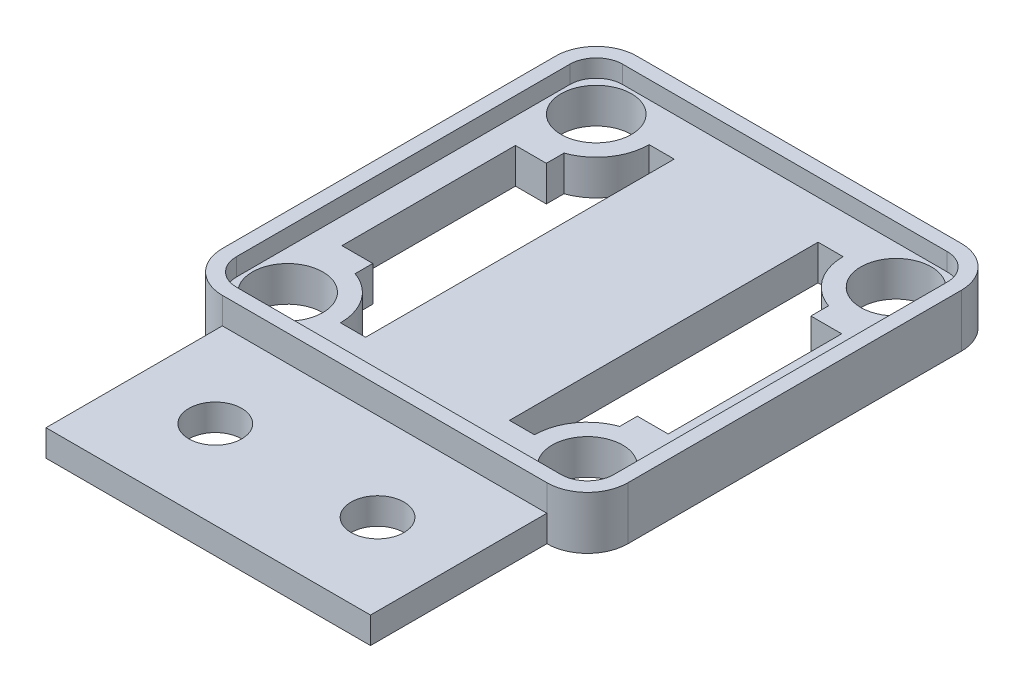
SolidWorks part; units mm, degrees
ref_plane "Front Plane" through (0, 0, 0) normal (0, 0, 1) x (1, 0, 0)
ref_plane "Top Plane" through (0, 0, 0) normal (0, 1, 0) x (1, 0, 0)
ref_plane "Right Plane" through (0, 0, 0) normal (1, 0, 0) x (0, 0, -1)
sketch "Sketch1" plane through (0, 0, 0) normal (0, 1, 0) x (1, 0, 0)
  line L1 (-12.6491, 14.6331) -> (5.7509, 14.6331)
  line L2 (-14.9491, 12.3331) -> (-14.9491, -6.5669)
  line L3 (-12.6491, -8.8669) -> (5.7509, -8.8669)
  line L4 (8.0509, 12.3331) -> (8.0509, -6.5669)
  line L5 (-14.9491, 14.6331) -> (8.0509, -8.8669) construction
  line L6 (-14.9491, -8.8669) -> (8.0509, 14.6331) construction
  arc A0 (8.0509, 12.3331) -> (5.7509, 14.6331) centre (5.7509, 12.3331) ccw
  arc A1 (-12.6491, -8.8669) -> (-14.9491, -6.5669) centre (-12.6491, -6.5669) cw
  arc A2 (5.7509, -8.8669) -> (8.0509, -6.5669) centre (5.7509, -6.5669) ccw
  arc A3 (-14.9491, 12.3331) -> (-12.6491, 14.6331) centre (-12.6491, 12.3331) cw
  point P0 (-3.4491, 2.8831)
  dimension "D3" = 2.3
  dimension "D4" = 2.3
  dimension "D1" = 23.5
  dimension "D2" = 23
extrude "Boss-Extrude1" add sketch "Sketch1" along normal blind 3
sketch "Sketch2" plane through (0, 3, 0) normal (0, 1, 0) x (1, 0, 0)
  line L8 (5.7509, 13.6331) -> (-12.6491, 13.6331)
  line L9 (-13.9491, 12.3331) -> (-13.9491, -6.5669)
  line L10 (-12.6491, -7.8669) -> (5.7509, -7.8669)
  line L11 (7.0509, -6.5669) -> (7.0509, 12.3331)
  line L12 (5.7509, 13.6331) -> (-12.6491, 13.6331)
  line L13 (-13.9491, 12.3331) -> (-13.9491, -6.5669)
  line L14 (-12.6491, -7.8669) -> (5.7509, -7.8669)
  line L15 (7.0509, -6.5669) -> (7.0509, 12.3331)
  arc A8 (7.0509, 12.3331) -> (5.7509, 13.6331) centre (5.7509, 12.3331) ccw
  arc A9 (-12.6491, 13.6331) -> (-13.9491, 12.3331) centre (-12.6491, 12.3331) ccw
  arc A10 (-13.9491, -6.5669) -> (-12.6491, -7.8669) centre (-12.6491, -6.5669) ccw
  arc A11 (5.7509, -7.8669) -> (7.0509, -6.5669) centre (5.7509, -6.5669) ccw
  arc A12 (7.0509, 12.3331) -> (5.7509, 13.6331) centre (5.7509, 12.3331) ccw
  arc A13 (-12.6491, 13.6331) -> (-13.9491, 12.3331) centre (-12.6491, 12.3331) ccw
  arc A14 (-13.9491, -6.5669) -> (-12.6491, -7.8669) centre (-12.6491, -6.5669) ccw
  arc A15 (5.7509, -7.8669) -> (7.0509, -6.5669) centre (5.7509, -6.5669) ccw
  dimension "D1" = 1
extrude "Cut-Extrude2" cut sketch "Sketch2" against normal blind 1
sketch "Sketch5" plane through (0, 2, 0) normal (0, 1, 0) x (1, 0, 0)
  line L0 (-3.4491, 13.6331) -> (-3.4491, -7.8669) construction
  line L1 (5.7509, 13.6331) -> (-12.6491, 13.6331) construction
  line L2 (-12.6491, -7.8669) -> (5.7509, -7.8669) construction
  line L3 (7.0509, 2.8831) -> (-13.9491, 2.8831) construction
  line L4 (7.0509, -6.5669) -> (7.0509, 12.3331) construction
  line L5 (-13.9491, 12.3331) -> (-13.9491, -6.5669) construction
  circle A0 centre (5.0509, 11.6331) radius 2
  circle A1 centre (5.0509, -5.8669) radius 2
  circle A2 centre (-11.9491, -5.8669) radius 2
  circle A3 centre (-11.9491, 11.6331) radius 2
  dimension "D1" = 4
extrude "Cut-Extrude3" cut sketch "Sketch5" against normal through all
sketch "Sketch6" plane through (0, 2, 0) normal (0, 1, 0) x (1, 0, 0)
  line L0 (-14.9491, 12.3331) -> (-14.9491, -6.5669) construction
  line L1 (8.0509, -6.5669) -> (8.0509, 12.3331) construction
  line L14 (4.0509, -5.8669) -> (4.0509, 11.6331)
  line L15 (4.0509, -3.0385) -> (4.0509, 8.8047)
  line L16 (2.0509, 11.6331) -> (2.0509, -5.8669)
  line L17 (-10.9491, 12.3331) -> (-10.9491, -6.5669)
  line L18 (-10.9491, 8.8047) -> (-10.9491, -3.0385)
  line L19 (-8.9491, 11.6331) -> (-8.9491, -5.8669)
  arc A5 (-11.9491, -8.8669) -> (-14.9491, -5.8669) centre (-11.9491, -5.8669) ccw
  arc A6 (-8.9491, -5.8669) -> (-10.9491, -3.0385) centre (-11.9491, -5.8669) ccw
  arc A20 (5.0509, 14.6331) -> (8.0509, 11.6331) centre (5.0509, 11.6331) ccw
  arc A21 (2.0509, 11.6331) -> (4.0509, 8.8047) centre (5.0509, 11.6331) ccw
  arc A23 (-14.9491, 11.6331) -> (-11.9491, 14.6331) centre (-11.9491, 11.6331) ccw
  arc A24 (-10.9491, 8.8047) -> (-8.9491, 11.6331) centre (-11.9491, 11.6331) ccw
  arc A26 (8.0509, -5.8669) -> (5.0509, -8.8669) centre (5.0509, -5.8669) ccw
  arc A27 (4.0509, -3.0385) -> (2.0509, -5.8669) centre (5.0509, -5.8669) ccw
  dimension "D1" = 23
  dimension "D2" = 1
  dimension "D3" = 1
  dimension "D4" = 1
  dimension "D5" = 1
  dimension "D6" = 3
  dimension "D7" = 3
extrude "Cut-Extrude4" cut sketch "Sketch6" against normal through all
sketch "Sketch7" plane through (0, 0, 8.8669) normal (0, 0, 1) x (1, 0, 0)
  line L0 (-14.9491, 3) -> (-14.9491, 0) construction
  line L1 (8.0509, 3) -> (8.0509, 0) construction
  line L2 (-12.6491, 3) -> (-12.6491, 0) construction
  line L3 (-12.6491, 1.5) -> (5.7509, 1.5)
  line L4 (5.7509, 3) -> (5.7509, 0) construction
  line L5 (5.7509, 1.5) -> (5.7509, 0)
  line L6 (5.7509, 0) -> (-12.6491, 0)
  line L7 (-12.6491, 0) -> (-12.6491, 1.5)
  dimension "D1" = 23
extrude "Boss-Extrude2" add sketch "Sketch7" along normal blind 10
sketch "Sketch8" plane through (0, 1.5, 0) normal (0, 1, 0) x (1, 0, 0)
  line L0 (-12.6491, -8.8669) -> (5.7509, -8.8669) construction
  line L1 (-12.6491, -18.8669) -> (-12.6491, -8.8669) construction
  line L2 (5.7509, -18.8669) -> (5.7509, -8.8669) construction
  line L3 (-3.4491, -8.8669) -> (-3.4491, -18.8669) construction
  line L4 (5.7509, -18.8669) -> (-12.6491, -18.8669) construction
  circle A0 centre (1.1509, -13.8669) radius 1.5
  circle A1 centre (-8.0491, -13.8669) radius 1.5
  dimension "D2" = 3
  dimension "D1" = 5
  dimension "D3" = 18.4
  dimension "D4" = 4.6
  dimension "D5" = 4.6
extrude "Cut-Extrude5" cut sketch "Sketch8" against normal through all
sketch "Sketch9" plane through (0, 3, 0) normal (0, 1, 0) x (1, 0, 0)
  line L8 (5.7509, 13.8331) -> (-12.6491, 13.8331)
  line L9 (-14.1491, 12.3331) -> (-14.1491, -6.5669)
  line L10 (-12.6491, -8.0669) -> (5.7509, -8.0669)
  line L11 (7.2509, -6.5669) -> (7.2509, 12.3331)
  line L12 (5.7509, 13.8331) -> (-12.6491, 13.8331)
  line L13 (-14.1491, 12.3331) -> (-14.1491, -6.5669)
  line L14 (-12.6491, -8.0669) -> (5.7509, -8.0669)
  line L15 (7.2509, -6.5669) -> (7.2509, 12.3331)
  arc A8 (7.2509, 12.3331) -> (5.7509, 13.8331) centre (5.7509, 12.3331) ccw
  arc A9 (-12.6491, 13.8331) -> (-14.1491, 12.3331) centre (-12.6491, 12.3331) ccw
  arc A10 (-14.1491, -6.5669) -> (-12.6491, -8.0669) centre (-12.6491, -6.5669) ccw
  arc A11 (5.7509, -8.0669) -> (7.2509, -6.5669) centre (5.7509, -6.5669) ccw
  arc A12 (7.2509, 12.3331) -> (5.7509, 13.8331) centre (5.7509, 12.3331) ccw
  arc A13 (-12.6491, 13.8331) -> (-14.1491, 12.3331) centre (-12.6491, 12.3331) ccw
  arc A14 (-14.1491, -6.5669) -> (-12.6491, -8.0669) centre (-12.6491, -6.5669) ccw
  arc A15 (5.7509, -8.0669) -> (7.2509, -6.5669) centre (5.7509, -6.5669) ccw
  dimension "D1" = 0.8
extrude "Cut-Extrude6" cut sketch "Sketch9" against normal blind 1
sketch "Sketch11" plane through (0, 2, 0) normal (0, 1, 0) x (1, 0, 0)
  line L0 (-8.9491, 11.6331) -> (-7.528, 11.6331)
  line L1 (-7.528, 11.6331) -> (-7.528, -5.8669)
  line L2 (-7.528, -5.8669) -> (-8.9491, -5.8669)
  line L3 (-8.9491, -5.8669) -> (-8.9491, 11.6331)
  line L4 (-3.4491, 13.8331) -> (-3.4491, -8.0669) construction
  line L5 (5.7509, 13.8331) -> (-12.6491, 13.8331) construction
  line L6 (-12.6491, -8.0669) -> (5.7509, -8.0669) construction
  line L7 (0.6299, -5.8669) -> (2.0509, -5.8669)
  line L8 (0.6299, 11.6331) -> (0.6299, -5.8669)
  line L9 (2.0509, 11.6331) -> (0.6299, 11.6331)
  line L10 (2.0509, -5.8669) -> (2.0509, 11.6331)
  line L11 (-10.9491, 8.8047) -> (-10.9491, -3.0385) construction
  line L12 (-12.6991, 7.8031) -> (-10.9491, 7.8031)
  line L13 (-12.6991, 7.8031) -> (-12.6991, -2.0369)
  line L14 (-12.6991, -2.0369) -> (-10.9491, -2.0369)
  line L15 (-10.9491, 7.8031) -> (-10.9491, -2.0369)
  line L16 (5.8009, -2.0369) -> (4.0509, -2.0369)
  line L17 (4.0509, 7.8031) -> (4.0509, -2.0369)
  line L18 (5.8009, 7.8031) -> (4.0509, 7.8031)
  line L19 (5.8009, 7.8031) -> (5.8009, -2.0369)
  point P22 (-10.9491, 2.8831)
  point P23 (-10.9491, 2.8831)
  dimension "D1" = 9.84
  dimension "D2" = 1.75
extrude "Cut-Extrude7" cut sketch "Sketch11" against normal through all
